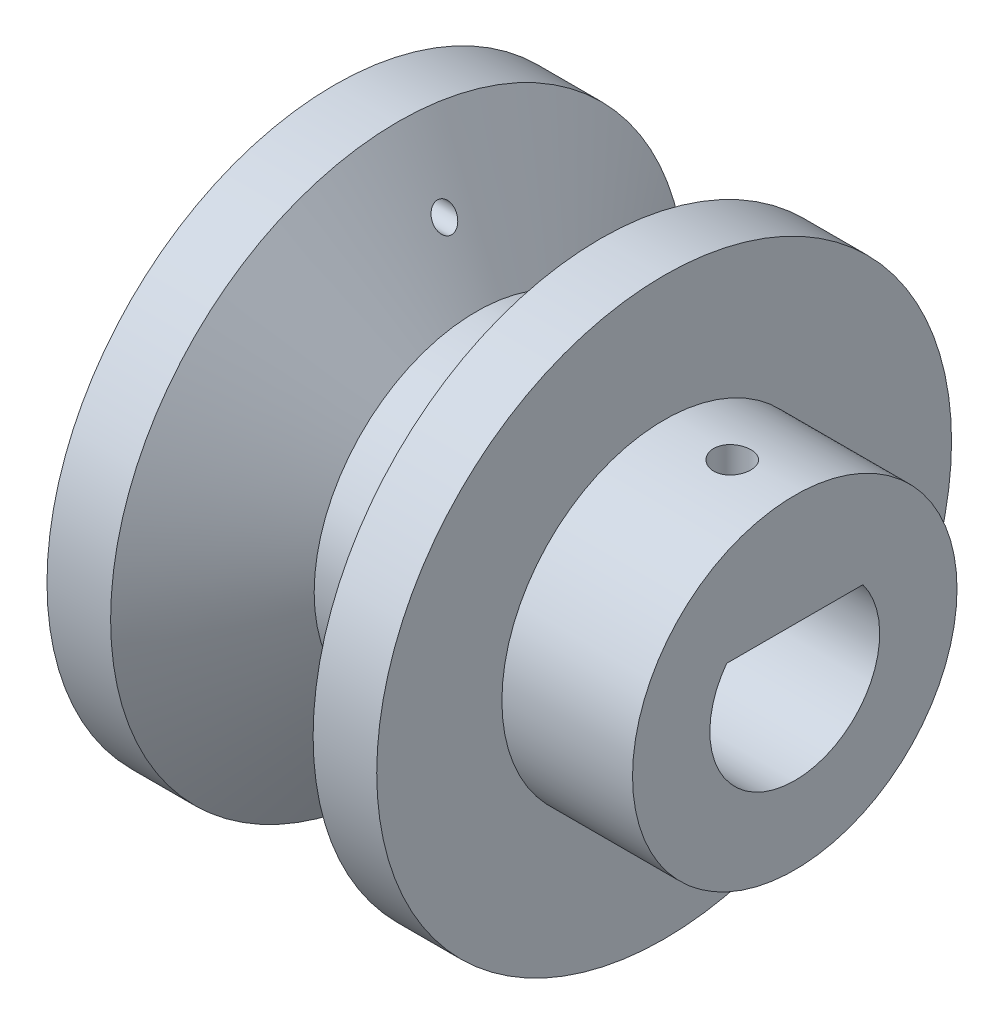
SolidWorks part; units mm, degrees
ref_plane "前基準面" through (0, 0, 0) normal (0, 0, 1) x (1, 0, 0)
ref_plane "上基準面" through (0, 0, 0) normal (0, 1, 0) x (1, 0, 0)
ref_plane "右基準面" through (0, 0, 0) normal (1, 0, 0) x (0, 0, -1)
sketch "草圖1" plane through (0, 0, 0) normal (0, 0, 1) x (1, 0, 0)
  line L0 (0, 0) -> (0, 22)
  line L1 (0, 22) -> (4.87, 22)
  line L2 (4.87, 22) -> (10.87, 12.4189)
  line L3 (10.87, 12.4189) -> (14.37, 12.4189)
  line L4 (14.37, 12.4189) -> (20.37, 22)
  line L5 (20.37, 22) -> (25.24, 22)
  line L6 (25.24, 22) -> (25.24, 12.4189)
  line L7 (25.24, 12.4189) -> (35.24, 12.4189)
  line L8 (35.24, 12.4189) -> (35.24, 0)
  line L9 (-743.1564, 0) -> (36475.4845, 0) construction
  line L10 (0, 0) -> (35.24, 0)
  dimension "D1" = 22
  dimension "D2" = 4.87
  dimension "D3" = 6
  dimension "D4" = 3.5
  dimension "D5" = 6
  dimension "D6" = 4.87
  dimension "D7" = 10
revolve "旋轉1" add sketch "草圖1" angle 360 about L9
ref_plane "平面1" through (0, 12, 0) normal (0, 1, 0) x (1, 0, 0)
sketch "草圖2" plane through (0, 12, 0) normal (0, 1, 0) x (1, 0, 0)
  circle A0 centre (30.4565, 0) radius 1.385
  dimension "D1" = 2.77
extrude "除料-伸長1" cut sketch "草圖2" against normal blind 10
sketch "草圖3" plane through (35.24, 0, 0) normal (1, 0, 0) x (0, 0, -1)
  circle A0 centre (0, 0) radius 6.5
  dimension "D1" = 13
extrude "除料-伸長2" cut sketch "草圖3" against normal blind 35
sketch "草圖5" plane through (0, 12, 0) normal (0, 1, 0) x (1, 0, 0)
  line L0 (-970.9285, 0) -> (49029.0715, 0) construction
  line L1 (30.4565, -998.615) -> (30.4565, 49001.385) construction
  circle A4 centre (30.4565, 0) radius 1.425
  dimension "D1" = 2.85
extrude "除料-伸長3" cut sketch "草圖5" against normal blind 10 and the other way blind 2
sketch "草圖11" plane through (35.24, 0, 0) normal (1, 0, 0) x (0, 0, -1)
  line L1 (-5.9062, 7.2825) -> (5.525, 7.2825)
  line L2 (-5.9062, 7.2825) -> (-5.9062, 3.8825)
  line L3 (-5.9062, 3.8825) -> (5.525, 3.8825)
  line L4 (5.525, 7.2825) -> (5.525, 3.8825)
  circle A0 centre (0, 0) radius 12.4189 construction
  dimension "D1" = 3.4
  dimension "D2" = 7.2825
  dimension "D3" = 11.4312
extrude "填料-伸長3" add sketch "草圖11" against normal blind 35
sketch "草圖13" plane through (0, 12, 0) normal (0, 1, 0) x (1, 0, 0)
  circle A0 centre (30.4565, 0) radius 1.425
extrude "除料-伸長4" cut sketch "草圖13" against normal blind 16
sketch "草圖14" plane through (0, 0, 0) normal (-1, 0, 0) x (0, 0, 1)
  circle A0 centre (-0.4353, 17.0039) radius 0.8774
extrude "除料-伸長5" cut sketch "草圖14" against normal blind 12
ref_plane "平面2" through (0, 22, 0) normal (0, 1, 0) x (1, 0, 0)
